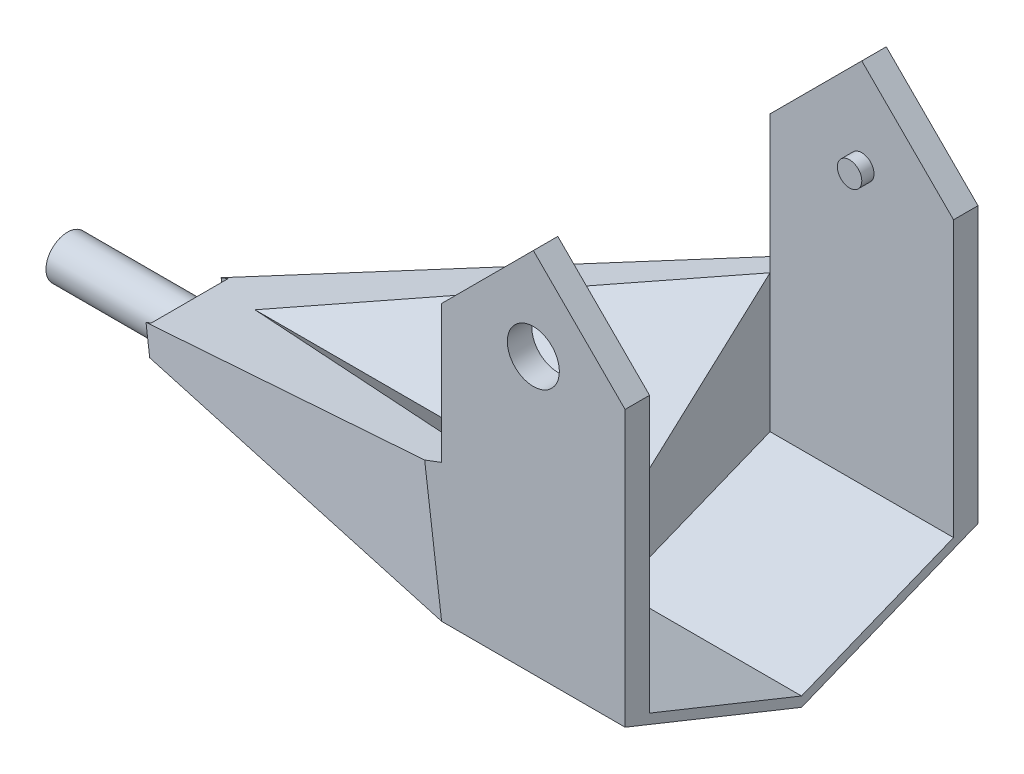
SolidWorks part; units mm, degrees
ref_plane "Front Plane" through (0, 0, 0) normal (0, 0, 1) x (1, 0, 0)
ref_plane "Top Plane" through (0, 0, 0) normal (0, 1, 0) x (1, 0, 0)
ref_plane "Right Plane" through (0, 0, 0) normal (1, 0, 0) x (0, 0, -1)
sketch "Sketch1" plane through (0, 0, 0) normal (0, 0, 1) x (1, 0, 0)
  line L3 (0, 10) -> (0, -15)
  line L9 (-30, 10) -> (-30, -35)
  line L14 (-15, 25) -> (0, 10)
  line L15 (-30, 10) -> (-15, 25)
  line L16 (0, -15) -> (-30, -35)
  circle A1 centre (-15, 10) radius 4.25
  dimension "D1" = 30
  dimension "D2" = 8.5
ref_plane "Plane1" through (0, 0, -49.7) normal (0, 0, 1) x (1, 0, 0)
sketch "Sketch2" plane through (0, 0, -49.7) normal (0, 0, 1) x (1, 0, 0)
  line L0 (-30, -35) -> (-30, 10)
  line L1 (-30, 10) -> (-15, 25)
  line L2 (-15, 25) -> (0, 10)
  line L3 (0, 10) -> (0, -15)
  line L4 (0, -15) -> (-30, -35)
sketch "Sketch3" plane through (0, 0, -49.7) normal (0, 0, 1) x (1, 0, 0)
  circle A0 centre (-15, 10) radius 2
extrude "Boss-Extrude1" add sketch "Sketch1" along normal blind 4
extrude "Boss-Extrude2" add sketch "Sketch2" against normal blind 4
extrude "Boss-Extrude3" add sketch "Sketch3" along normal blind 2
sketch "Sketch4" plane through (0, 0, -49.7) normal (0, 0, 1) x (1, 0, 0)
  line L0 (-30, -35) -> (0, -35)
  line L1 (0, -31.735) -> (0, 31.735) construction
  line L2 (0, -35) -> (0, -15)
  line L3 (-30, -35) -> (0, -15) construction
  line L4 (0, -15) -> (-30, -35)
extrude "Boss-Extrude4" add sketch "Sketch4" along normal blind 53.7 and the other way blind 4
sketch "Sketch5" plane through (0, 0, 0) normal (1, 0, 0) x (0, 0, -1)
  line L0 (24.85, -15) -> (49.7, -15)
  line L1 (49.7, -15) -> (0, -15) construction
  line L2 (49.7, 16.5) -> (49.7, -16.5) construction
  line L3 (49.7, -15) -> (49.7, -35)
  line L4 (53.7, -35) -> (-4, -35) construction
  line L5 (49.7, -35) -> (0, -35)
  line L6 (0, 16.5) -> (0, -16.5) construction
  line L7 (0, -35) -> (0, -15)
  line L8 (0, -15) -> (24.85, -15)
extrude "Cut-Extrude1" cut sketch "Sketch5" against normal blind 53.7
sketch "Sketch6" plane through (0, 0, 0) normal (1, 0, 0) x (0, 0, -1)
  line L0 (0, -35) -> (-4, -35)
  line L1 (0, 10) -> (0, -35) construction
  line L3 (49.7, 16.5) -> (49.7, -16.5) construction
  line L4 (49.7, -35) -> (53.7, -35)
  line L5 (53.7, -35) -> (49.7, -35) construction
  line L7 (24.85, -45) -> (49.7, -35)
  line L8 (24.85, -45) -> (0, -35)
  line L9 (-4, -35) -> (24.85, -46.6097)
  line L10 (53.7, -35) -> (24.85, -46.6097)
extrude "Boss-Extrude5" add sketch "Sketch6" against normal blind 120
sketch "Sketch7" plane through (0, 0, -49.7) normal (0, 0, 1) x (1, 0, 0)
  line L0 (-30, -35) -> (-120, -35)
  line L1 (-120, -35) -> (-120, -46.6097)
  line L2 (-120, -46.6097) -> (-30, -35)
extrude "Cut-Extrude2" cut sketch "Sketch7" along normal blind 120 and the other way blind 120
sketch "Sketch8" plane through (0, 0, -49.7) normal (0, 0, 1) x (1, 0, 0)
  line L0 (-30, -35) -> (-30, -12.5)
  line L1 (-30, 10) -> (-30, -35) construction
  line L2 (-30, -12.5) -> (-120, -46.6097)
  line L3 (-120, -46.6097) -> (-30, -35)
extrude "Boss-Extrude6" add sketch "Sketch8" along normal blind 53.7 and the other way blind 4
sketch "Sketch9" plane through (3.9499, -30.6206, 0) normal (0.1279, -0.9918, 0) x (0.9918, 0.1279, 0)
  line L0 (-124.9769, -24.85) -> (-34.2312, -53.7)
  line L1 (-124.9769, -24.85) -> (-5.9631, -24.85) construction
  line L2 (-34.2312, -53.7) -> (-124.9769, -24.85) construction
  line L3 (-34.2312, -53.7) -> (-124.9769, -53.7)
  line L4 (-124.9769, -53.7) -> (-34.2312, -53.7) construction
  line L5 (-124.9769, -53.7) -> (-124.9769, -24.85)
extrude "Cut-Extrude3" cut sketch "Sketch9" against normal blind 53.7
sketch "Sketch10" plane through (3.9499, -30.6206, 0) normal (0.1279, -0.9918, 0) x (0.9918, 0.1279, 0)
  line L0 (-124.9769, -24.85) -> (-34.2312, 4)
  line L1 (-124.9769, -24.85) -> (-5.9631, -24.85) construction
  line L2 (-124.9769, -24.85) -> (-34.2312, 4) construction
  line L3 (-34.2312, 4) -> (-124.9769, 4)
  line L4 (-124.9769, 4) -> (-34.2312, 4) construction
  line L5 (-124.9769, 4) -> (-124.9769, -24.85)
extrude "Cut-Extrude4" cut sketch "Sketch10" against normal blind 53.7
ref_plane "Plane2" through (-100, 0, 0) normal (1, 0, 0) x (0, 0, -1)
sketch "Sketch18" plane through (-100, 0, 0) normal (1, 0, 0) x (0, 0, -1)
  line L1 (31.0909, -51.1717) -> (18.5152, -51.1717)
  line L2 (31.0909, -51.1717) -> (31.0909, -38.9735)
  line L3 (31.0909, -38.9735) -> (18.5152, -38.9735)
  line L4 (18.5152, -51.1717) -> (18.5152, -38.9735)
  line L5 (31.0909, -51.1717) -> (18.5152, -38.9735) construction
  line L6 (31.0909, -38.9735) -> (18.5152, -51.1717) construction
  point P0 (24.803, -45.0726)
extrude "Cut-Extrude9" cut sketch "Sketch18" against normal blind 98.7
sketch "Sketch19" plane through (-100, 0, 0) normal (-1, 0, 0) x (0, 0, 1)
  line L0 (-31.0909, -39.0297) -> (-31.0909, -44.0982)
  line L1 (-31.0909, -44.0982) -> (-24.85, -46.6097)
  line L2 (-24.85, -46.6097) -> (-18.5152, -44.0604)
  line L3 (-18.5152, -44.0604) -> (-18.5152, -39.0297)
  line L4 (-18.5152, -39.0297) -> (-31.0909, -39.0297)
extrude "Boss-Extrude7" add sketch "Sketch19" along normal blind 20
sketch "Sketch20" plane through (-120, 0, 0) normal (-1, 0, 0) x (0, 0, 1)
  line L0 (-24.803, -39.0297) -> (-24.85, -46.6097)
  line L1 (-18.5152, -39.0297) -> (-31.0909, -39.0297) construction
  circle A1 centre (-24.8265, -42.8197) radius 3.5088
  line M2 (-18.5152, -39.0297) -> (-31.0909, -39.0297)
  line M3 (-31.0909, -39.0297) -> (-31.0909, -44.0982)
  line M4 (-31.0909, -44.0982) -> (-24.85, -46.6097)
  line M5 (-24.85, -46.6097) -> (-18.5152, -44.0604)
  line M6 (-18.5152, -44.0604) -> (-18.5152, -39.0297)
extrude "Cut-Extrude11" cut sketch "Sketch20" against normal blind 20 contours A1 L0 M5 M6 M2 | A1 L0 M2 M3 M4 | A1 L0 M5
sketch "Sketch22" plane through (-120, 0, 0) normal (-1, 0, 0) x (0, 0, 1)
  circle A0 centre (-24.8265, -42.8197) radius 3
extrude "Cut-Extrude12" cut sketch "Sketch22" against normal blind 10
sketch "Sketch23" plane through (-30, 0, 0) normal (1, 0, 0) x (0, 0, -1)
  line L0 (0, -12.5) -> (49.7, -12.5)
  line L1 (0, 39.3853) -> (0, -39.3853) construction
  line L2 (49.7, -12.5) -> (0, -12.5) construction
  line L3 (49.7, 39.3853) -> (49.7, -39.3853) construction
  line L4 (49.7, -12.5) -> (49.7, -34.9446)
  line L5 (49.7, -34.9446) -> (0, -34.9446)
  line L6 (0, -34.9446) -> (0, -12.5)
  line L7 (24.3006, -23.7223) -> (49.7, -12.5)
  line L8 (0, -12.5) -> (24.3006, -23.7223)
  line M3 (49.7, -12.5) -> (0, -12.5)
extrude "Cut-Extrude13" cut sketch "Sketch23" against normal blind 99 contours L8 L7 M3
sketch "Sketch24" plane through (-30, 0, 0) normal (1, 0, 0) x (0, 0, -1)
  line L0 (0, -12.5) -> (24.85, -35)
  line L1 (0, 39.3853) -> (0, -39.3853) construction
  line L2 (0, -12.5) -> (24.3006, -23.7223) construction
  line L3 (49.7, -35) -> (0, -35) construction
  line L4 (24.85, -35) -> (49.7, -12.5)
  line L5 (49.7, 39.3853) -> (49.7, -39.3853) construction
  line L6 (24.3006, -23.7223) -> (49.7, -12.5) construction
  line L7 (49.7, -12.5) -> (24.3006, -23.7223)
  line L8 (24.3006, -23.7223) -> (0, -12.5)
extrude "Cut-Extrude14" cut sketch "Sketch24" against normal blind 99
ref_plane "Plane3" through (-30, 0, 0) normal (1, 0, 0) x (0, 0, -1)
sketch "Sketch25" plane through (-30, 0, 0) normal (1, 0, 0) x (0, 0, -1)
  line L0 (0, -35) -> (49.7, -35)
  line L1 (0, 39.3853) -> (0, -39.3853) construction
  line L2 (49.7, 39.3853) -> (49.7, -39.3853) construction
  line L3 (49.7, -35) -> (24.85, -45)
  line L4 (24.85, -45) -> (0, -35)
extrude "Boss-Extrude8" add sketch "Sketch25" against normal blind 12
